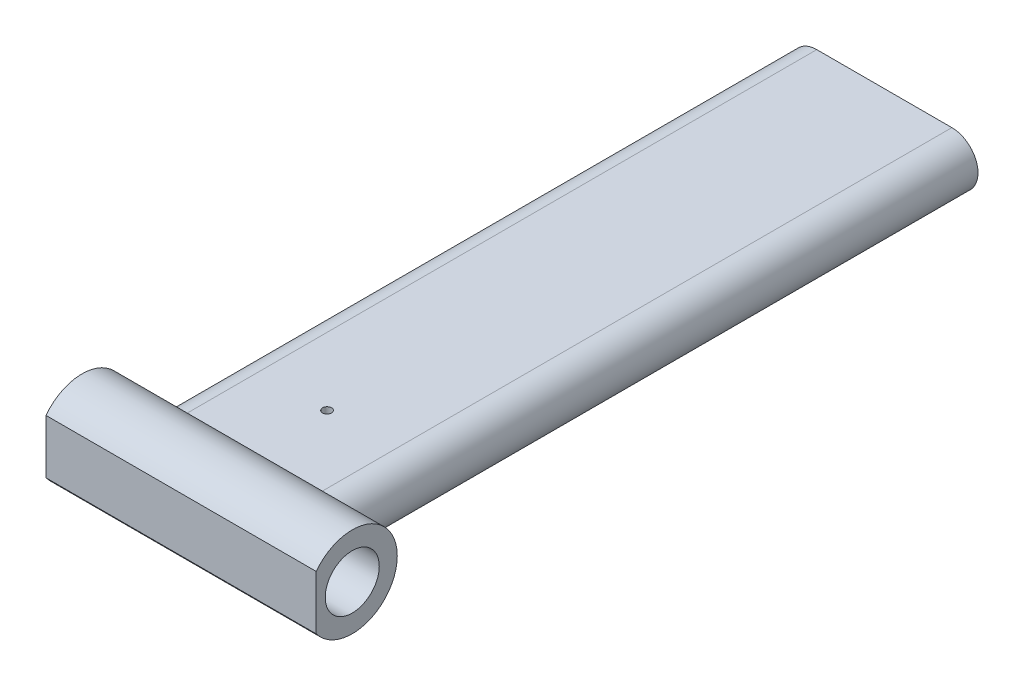
SolidWorks part; units mm, degrees
ref_plane "Front Plane" through (0, 0, 0) normal (0, 0, 1) x (1, 0, 0)
ref_plane "Top Plane" through (0, 0, 0) normal (0, 1, 0) x (1, 0, 0)
ref_plane "Right Plane" through (0, 0, 0) normal (1, 0, 0) x (0, 0, -1)
sketch "Sketch2" plane through (0, 0, 0) normal (0, 0, 1) x (1, 0, 0)
  line L0 (7.5, 0) -> (-7.5, 0) construction
  line L1 (7.5, -2.9) -> (-7.5, -2.9)
  line L2 (7.5, 2.9) -> (-7.5, 2.9)
  arc A0 (7.5, -2.9) -> (7.5, 2.9) centre (7.5, 0) ccw
  arc A1 (-7.5, 2.9) -> (-7.5, -2.9) centre (-7.5, 0) ccw
  point P2 (0, 0)
  dimension "D2" = 2.9
  dimension "D1" = 15
sketch "Sketch4" plane through (0, 0, 0) normal (0, 0, 1) x (1, 0, 0)
  line L0 (7.5, 0) -> (-7.5, 0) construction
  line L1 (7.5, -2.9) -> (-7.5, -2.9)
  line L2 (7.5, 2.9) -> (-7.5, 2.9)
  line L3 (7.5, -1.9) -> (-7.5, -1.9)
  line L4 (7.5, 1.9) -> (-7.5, 1.9)
  arc A0 (7.5, -2.9) -> (7.5, 2.9) centre (7.5, 0) ccw
  arc A1 (-7.5, 2.9) -> (-7.5, -2.9) centre (-7.5, 0) ccw
  arc A2 (-7.5, 1.9) -> (-7.5, -1.9) centre (-7.5, 0) ccw
  arc A3 (7.5, -1.9) -> (7.5, 1.9) centre (7.5, 0) ccw
  point P2 (0, 0)
  dimension "D2" = 2.9
  dimension "D3" = 1
  dimension "D1" = 15
extrude "Boss-Extrude1" add sketch "Sketch4" along normal mid plane 70
ref_plane "Plane1" through (7.5, 2.9, 35) normal (-1, 0, 0) x (0, 0, 1)
sketch "Sketch5" plane through (7.5, 2.9, 35) normal (-1, 0, 0) x (0, 0, 1)
  circle A0 centre (0.0586, -2.9) radius 3.8182
ref_plane "Plane2" through (-7.5, 2.9, -35) normal (-1, 0, 0) x (0, 0, 1)
sketch "Sketch7" plane through (0, 0, 0) normal (1, 0, 0) x (0, 0, -1)
  circle A0 centre (-32.2662, 0) radius 10.0939
sketch "Sketch9" plane through (0, 0, 0) normal (1, 0, 0) x (0, 0, -1)
  line L0 (-35, 2.9) -> (-35, -2.9) construction
  line L2 (-35, 2.9153) -> (-35, -2.8847) construction
  circle A0 centre (-39.0731, 0.0153) radius 5
  circle A1 centre (-39.0731, 0.0153) radius 3
  dimension "D1" = 10
  dimension "D2" = 6
extrude "Boss-Extrude3" add sketch "Sketch9" along normal mid plane 30 contours A0
sketch "Sketch10" plane through (0, 0, 0) normal (0, 1, 0) x (1, 0, 0)
  line L1 (-22.062, -43.0731) -> (17.6828, -43.0731)
  line L2 (-22.062, -43.0731) -> (-22.062, -50.023)
  line L3 (-22.062, -50.023) -> (17.6828, -50.023)
  line L4 (17.6828, -43.0731) -> (17.6828, -50.023)
  line L6 (-15, -44.0731) -> (15, -44.0731) construction
  dimension "D1" = 1
extrude "Cut-Extrude1" cut sketch "Sketch10" against normal mid plane 26
sketch "Sketch11" plane through (0, 2.9, 0) normal (0, 1, 0) x (1, 0, 0)
  circle A0 centre (0, -26.8702) radius 0.5
  dimension "D1" = 1
extrude "Cut-Extrude2" cut sketch "Sketch11" against normal through all
sketch "Sketch12" plane through (15, 0, 0) normal (1, 0, 0) x (0, 0, -1)
  circle A0 centre (-39.0731, 0.0153) radius 3
  dimension "D1" = 6
extrude "Cut-Extrude3" cut sketch "Sketch12" against normal through all
